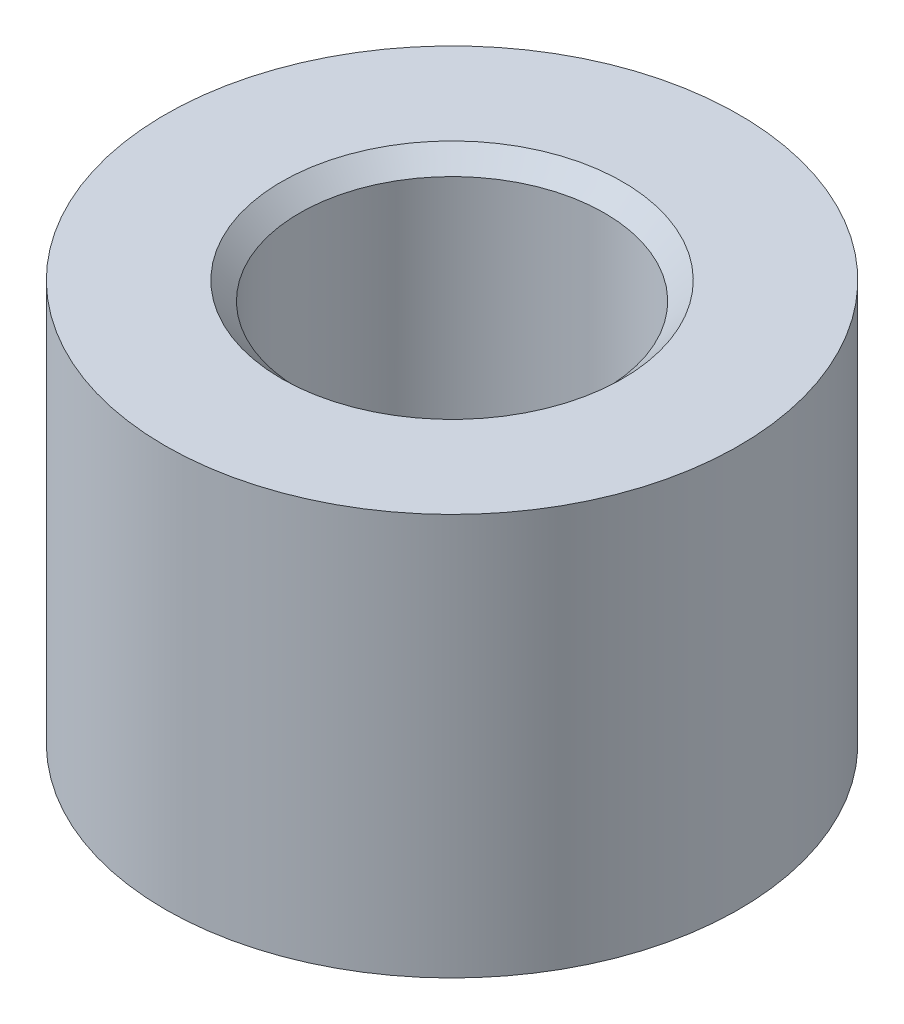
SolidWorks part; units mm, degrees
ref_plane "Front Plane" through (0, 0, 0) normal (0, 0, 1) x (1, 0, 0)
ref_plane "Top Plane" through (0, 0, 0) normal (0, 1, 0) x (1, 0, 0)
ref_plane "Right Plane" through (0, 0, 0) normal (1, 0, 0) x (0, 0, -1)
sketch "Sketch1" plane through (0, 0, 0) normal (0, 1, 0) x (1, 0, 0)
  circle A0 centre (0, 0) radius 3.375
  circle A1 centre (0, 0) radius 6.35
  dimension "D1" = 6.75
  dimension "D2" = 12.7
extrude "Boss-Extrude1" add sketch "Sketch1" along normal blind 8.8851
chamfer "Chamfer1" distance 0.4 angle 45 2 edges at (0, 0, 3.375) (0, 8.8851, 3.375)
